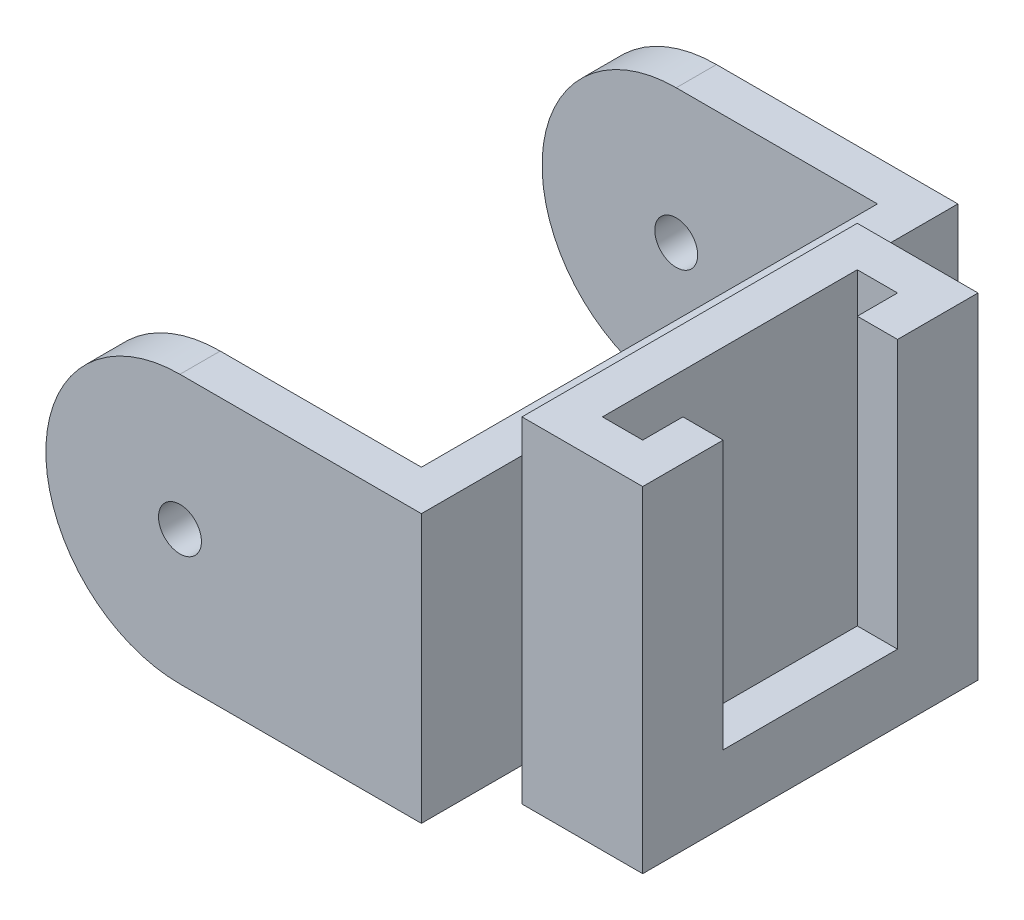
SolidWorks part; units mm, degrees
ref_plane "Plan de face" through (0, 0, 0) normal (0, 0, 1) x (1, 0, 0)
ref_plane "Plan de dessus" through (0, 0, 0) normal (0, 1, 0) x (1, 0, 0)
ref_plane "Plan de droite" through (0, 0, 0) normal (1, 0, 0) x (0, 0, -1)
sketch "Esquisse1" plane through (0, 0, 0) normal (1, 0, 0) x (0, 0, -1)
  line L1 (-20, 10) -> (20, 10)
  line L2 (-20, 10) -> (-20, -10)
  line L3 (-20, -10) -> (20, -10)
  line L4 (20, 10) -> (20, -10)
  line L5 (-20, 10) -> (20, -10) construction
  line L6 (-20, -10) -> (20, 10) construction
  point P0 (0, 0)
  dimension "D1" = 40
  dimension "D2" = 20
extrude "Boss.-Extru.1" add sketch "Esquisse1" along normal blind 3
sketch "Esquisse2" plane through (0, 0, 0) normal (-1, 0, 0) x (0, 0, 1)
  line L0 (20, -10) -> (-20, -10) construction
  line L1 (-20, 10) -> (-17, 10)
  line L2 (-20, 10) -> (-20, -10)
  line L3 (-20, -10) -> (-17, -10)
  line L4 (-17, 10) -> (-17, -10)
  line L6 (20, 10) -> (17, 10)
  line L7 (20, 10) -> (20, -10)
  line L8 (20, -10) -> (17, -10)
  line L9 (17, 10) -> (17, -10)
  dimension "D1" = 3
  dimension "D2" = 3
extrude "Boss.-Extru.2" add sketch "Esquisse2" along normal blind 25
sketch "Esquisse3" plane through (0, 0, 20) normal (0, 0, 1) x (1, 0, 0)
  line L0 (3, 10) -> (-25, 10) construction
  line L1 (3, -10) -> (-25, -10) construction
  line L2 (-25, -10) -> (-25, 10) construction
  line L3 (-15, 10) -> (-25, 10)
  line L4 (-25, 10) -> (-25, -10)
  line L5 (-25, -10) -> (-15, -10)
  arc A0 (-15, 10) -> (-15, -10) centre (-15, 0) ccw
  line M1 (3, 10) -> (-25, 10)
  line M2 (-25, 10) -> (-25, -10)
  line M3 (-25, -10) -> (3, -10)
  dimension "D1" = 10
extrude "Enlèv. mat.-Extru.1" cut sketch "Esquisse3" against normal blind 48 contours A0 M1 M2 | A0 L4 M3
sketch "Esquisse4" plane through (0, 0, 20) normal (0, 0, 1) x (1, 0, 0)
  circle A0 centre (-15, 0) radius 1.6
  dimension "D1" = 3.2
extrude "Enlèv. mat.-Extru.2" cut sketch "Esquisse4" against normal blind 48
sketch "Esquisse5" plane through (3, 0, 0) normal (1, 0, 0) x (0, 0, -1)
  line L1 (-12.5, 12.5) -> (12.5, 12.5)
  line L2 (-12.5, 12.5) -> (-12.5, -12.5)
  line L3 (-12.5, -12.5) -> (12.5, -12.5)
  line L4 (12.5, 12.5) -> (12.5, -12.5)
  line L5 (-12.5, 12.5) -> (12.5, -12.5) construction
  line L6 (-12.5, -12.5) -> (12.5, 12.5) construction
  point P0 (0, 0)
  dimension "D1" = 25
  dimension "D2" = 25
extrude "Boss.-Extru.3" add sketch "Esquisse5" along normal blind 9
sketch "Esquisse6" plane through (0, 12.5, 0) normal (0, 1, 0) x (1, 0, 0)
  line L0 (9, 9.5) -> (6, 9.5)
  line L3 (6, 9.5) -> (6, -9.5)
  line L4 (6, -9.5) -> (9, -9.5)
  line L5 (9, -9.5) -> (9, 9.5)
  line L6 (3, 12.5) -> (3, -12.5)
  line L7 (3, -12.5) -> (12, -12.5)
  line L8 (12, -12.5) -> (12, 12.5)
  line L9 (12, 12.5) -> (3, 12.5)
  line L10 (3, 12.5) -> (3, -12.5)
  line L11 (3, -12.5) -> (12, -12.5)
  line L12 (12, -12.5) -> (12, 12.5)
  line L13 (12, 12.5) -> (3, 12.5)
  dimension "D1" = 0
  dimension "D2" = 3
extrude "Enlèv. mat.-Extru.4" cut sketch "Esquisse6" against normal blind 23 contours L0 L3 L4 L5
sketch "Esquisse8" plane through (12, 0, 0) normal (1, 0, 0) x (0, 0, -1)
  line L0 (-6.5, -7.5) -> (6.5, -7.5)
  line L1 (-6.5, 12.5) -> (-6.5, -7.5)
  line L2 (6.5, 12.5) -> (6.5, -7.5)
  line L4 (9.5, 12.5) -> (-9.5, 12.5)
  line L5 (9.5, -10.5) -> (9.5, 12.5)
  line L6 (-9.5, -10.5) -> (9.5, -10.5)
  line L7 (-9.5, 12.5) -> (-9.5, -10.5)
  line L8 (6.5, 12.5) -> (-6.5, 12.5)
  dimension "D1" = 0
extrude "Enlèv. mat.-Extru.5" cut sketch "Esquisse8" against normal blind 3
